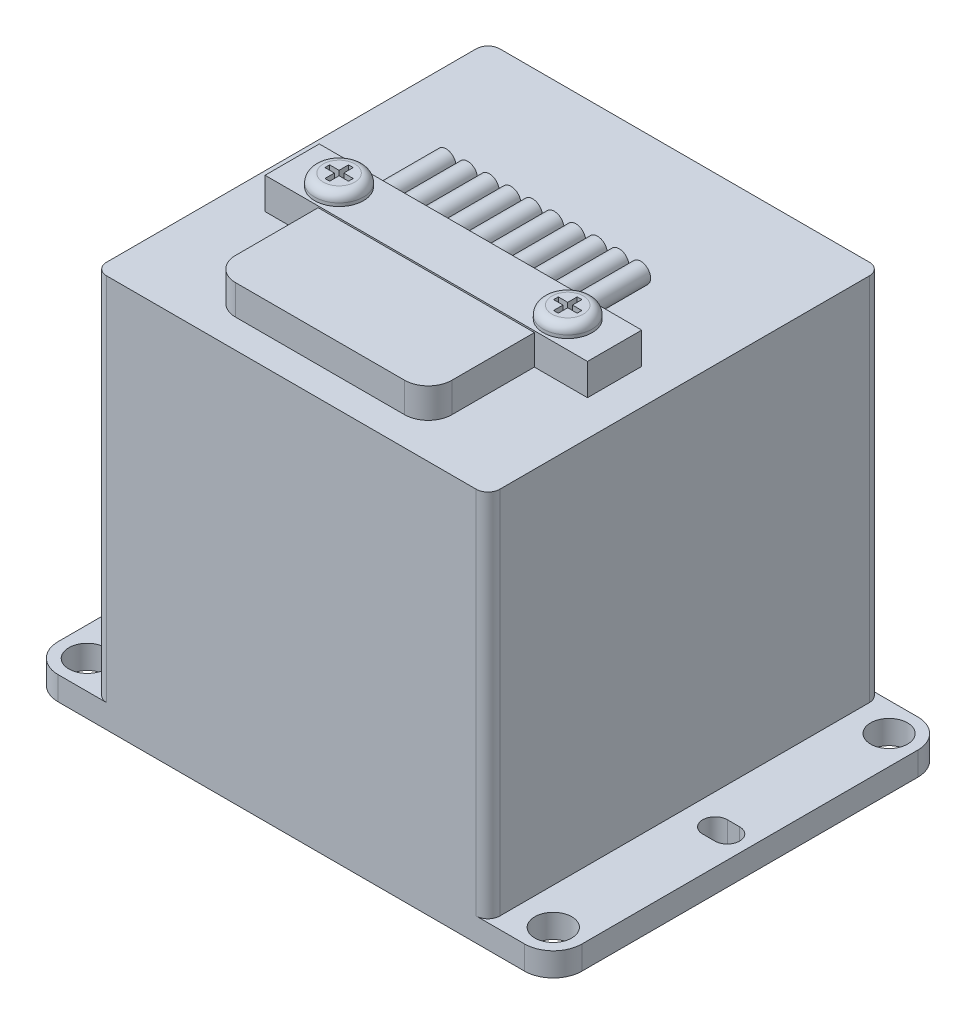
SolidWorks part; units mm, degrees
ref_plane "Front Plane" through (0, 0, 0) normal (0, 0, 1) x (1, 0, 0)
ref_plane "Top Plane" through (0, 0, 0) normal (0, 1, 0) x (1, 0, 0)
ref_plane "Right Plane" through (0, 0, 0) normal (1, 0, 0) x (0, 0, -1)
sketch "Sketch1" plane through (0, 0, 0) normal (0, 1, 0) x (1, 0, 0)
  line L1 (-16.9164, -12.7) -> (16.9164, -12.7)
  line L2 (-16.9164, -12.7) -> (-16.9164, 12.7)
  line L3 (-16.9164, 12.7) -> (16.9164, 12.7)
  line L4 (16.9164, -12.7) -> (16.9164, 12.7)
  line L5 (-16.9164, -12.7) -> (16.9164, 12.7) construction
  line L6 (-16.9164, 12.7) -> (16.9164, -12.7) construction
  point P0 (0, 0)
  dimension "D1" = 33.8328
  dimension "D2" = 25.4
extrude "Boss-Extrude1" add sketch "Sketch1" along normal blind 1.524
fillet "Fillet1" radius 1.8542 4 edges at (-16.9164, 0.762, 12.7) (-16.9164, 0.762, -12.7) (16.9164, 0.762, -12.7) (16.9164, 0.762, 12.7)
sketch "Sketch2" plane through (0, 1.524, 0) normal (0, 1, 0) x (1, 0, 0)
  line L1 (22.9238, 0) -> (-20.7739, 0) construction
  line L2 (15.4559, -0.8001) -> (14.6685, -0.8001)
  line L3 (15.4559, 0.8001) -> (14.6685, 0.8001)
  line L4 (16.256, 0) -> (13.8684, 0) construction
  line L5 (15.4559, 0.8001) -> (14.6685, -0.8001) construction
  circle A0 centre (15.0622, -10.8458) radius 1.1938
  circle A1 centre (15.0622, 10.8458) radius 1.1938
  circle A2 centre (-15.0368, 10.8458) radius 1.1938
  circle A3 centre (-15.0368, -10.8458) radius 1.1938
  circle A4 centre (-15.0368, 0) radius 0.8001
  arc A5 (15.4559, -0.8001) -> (15.4559, 0.8001) centre (15.4559, 0) ccw
  arc A6 (14.6685, 0.8001) -> (14.6685, -0.8001) centre (14.6685, 0) ccw
  point P26 (15.0622, 0)
  dimension "D1" = 2.3876
  dimension "D2" = 30.099
  dimension "D3" = 21.6916
  dimension "D4" = 1.6002
  dimension "D5" = 2.3876
  dimension "D6" = 1.6002
extrude "Cut-Extrude1" cut sketch "Sketch2" against normal blind 1.524
sketch "Sketch3" plane through (0, 1.524, 0) normal (0, 1, 0) x (1, 0, 0)
  line L0 (15.0622, 12.7) -> (-15.0622, 12.7) construction
  line L1 (-12.7, -12.7) -> (12.7, -12.7)
  line L2 (-12.7, -12.7) -> (-12.7, 12.7)
  line L3 (-12.7, 12.7) -> (12.7, 12.7)
  line L4 (12.7, -12.7) -> (12.7, 12.7)
  line L5 (-12.7, -12.7) -> (12.7, 12.7) construction
  line L6 (-12.7, 12.7) -> (12.7, -12.7) construction
  point P0 (0, 0)
  dimension "D1" = 25.4
extrude "Boss-Extrude2" add sketch "Sketch3" along normal blind 23.876
fillet "Fillet2" radius 0.762 4 edges
sketch "Sketch4" plane through (0, 25.4, 0) normal (0, 1, 0) x (1, 0, 0)
  line L0 (0, -21.1361) -> (0, 22.6474) construction
  line L1 (10.414, -3.9878) -> (-10.414, -3.9878)
  line L2 (10.414, -3.9878) -> (10.414, -0.4826)
  line L3 (10.414, -0.4826) -> (-10.414, -0.4826)
  line L4 (-10.414, -3.9878) -> (-10.414, -0.4826)
  line L5 (6.985, -3.9878) -> (-6.985, -3.9878)
  circle A0 centre (15.0622, -10.8458) radius 1.1938 construction
  dimension "D1" = 6.858
  dimension "D4" = 20.828
  dimension "D5" = 3.5052
extrude "Boss-Extrude3" add sketch "Sketch4" along normal blind 2.032 contours L0 L1 L2 L3 | L5 L0 L3 L4 L1
sketch "Sketch5" plane through (0, 25.4, 0) normal (0, 1, 0) x (1, 0, 0)
  line L0 (10.414, -3.9878) -> (-10.414, -3.9878) construction
  line L1 (6.985, -3.9878) -> (-6.985, -3.9878)
  line L2 (6.985, -3.9878) -> (6.985, -10.8458)
  line L3 (6.985, -10.8458) -> (-6.985, -10.8458)
  line L4 (-6.985, -3.9878) -> (-6.985, -10.8458)
  line L5 (0, -21.6155) -> (0, 18.5425) construction
  line L6 (0, 0) -> (0, -16.8235) construction
  dimension "D1" = 6.858
  dimension "D2" = 13.97
extrude "Boss-Extrude4" add sketch "Sketch5" along normal blind 1.9304
fillet "Fillet3" radius 1.524 2 edges at (-6.985, 26.3652, 10.8458) (6.985, 26.3652, 10.8458)
sketch "Sketch6" plane through (0, 0, 0.4826) normal (0, 0, -1) x (-1, 0, 0)
  line L3 (0, 36.3189) -> (0, -1.8757) construction
  circle A0 centre (-4.8895, 26.5554) radius 0.635
  circle A1 centre (3.4925, 26.5554) radius 0.635
  circle A2 centre (4.8895, 26.5554) radius 0.635
  circle A3 centre (2.0955, 26.5554) radius 0.635
  circle A4 centre (-2.0955, 26.5554) radius 0.635
  circle A5 centre (0.6985, 26.5554) radius 0.635
  circle A6 centre (-3.4925, 26.5554) radius 0.635
  circle A7 centre (-0.6985, 26.5554) radius 0.635
  circle A8 centre (-6.2865, 26.5554) radius 0.635
  circle A9 centre (6.2865, 26.5554) radius 0.635
  dimension "D1" = 1.27
  dimension "D3" = 1.397
  dimension "D4" = 1.397
  dimension "D5" = 1.397
  dimension "D6" = 1.397
  dimension "D7" = 1.397
  dimension "D8" = 1.397
  dimension "D9" = 1.397
  dimension "D10" = 1.397
  dimension "D2" = 1.397
extrude "Boss-Extrude5" add sketch "Sketch6" along normal blind 4.064
sketch "Sketch7" plane through (0, 27.432, 0) normal (0, 1, 0) x (1, 0, 0)
  line L0 (0, -5.518) -> (0, 6.6896) construction
  line L3 (10.414, -2.2352) -> (-10.414, -2.2352) construction
  line L4 (10.414, -3.9878) -> (10.414, -0.4826) construction
  line L5 (-10.414, -3.9878) -> (-10.414, -0.4826) construction
  circle A0 centre (7.3853, -2.2352) radius 1.5761
  circle A1 centre (-7.3853, -2.2352) radius 1.5761
extrude "Boss-Extrude6" add sketch "Sketch7" along normal blind 0.762
fillet "Fillet4" radius 0.5588 2 edges at (-7.3853, 28.194, 3.8113) (7.3853, 28.194, 3.8113)
sketch "Sketch8" plane through (0, 28.194, 0) normal (0, 1, 0) x (1, 0, 0)
  line L0 (8.4026, -2.2352) -> (8.1473, -2.2352) construction
  line L1 (-7.3853, -3.2525) -> (-7.3853, -2.9972) construction
  line L2 (7.3853, -3.2525) -> (7.3853, -2.9972) construction
  line L3 (7.5377, -1.4732) -> (7.5377, -2.0828)
  line L4 (7.5377, -1.4732) -> (7.2329, -1.4732)
  line L5 (7.5377, -2.9972) -> (7.2329, -2.9972)
  line L6 (7.2329, -1.4732) -> (7.2329, -2.0828)
  line L7 (-7.2329, -2.3876) -> (-6.6233, -2.3876)
  line L9 (6.6233, -2.3876) -> (7.2329, -2.3876)
  line L10 (6.6233, -2.3876) -> (6.6233, -2.0828)
  line L11 (8.1473, -2.3876) -> (8.1473, -2.0828)
  line L12 (6.6233, -2.0828) -> (7.2329, -2.0828)
  line L13 (-8.1473, -2.2352) -> (-8.4026, -2.2352) construction
  line L14 (-7.5377, -2.3876) -> (-7.5377, -2.9972)
  line L15 (-7.3853, -3.2525) -> (-7.3853, -2.9972) construction
  line L16 (-7.2329, -1.4732) -> (-7.2329, -2.0828)
  line L17 (-7.2329, -1.4732) -> (-7.5377, -1.4732)
  line L18 (-7.2329, -2.9972) -> (-7.5377, -2.9972)
  line L19 (-7.5377, -1.4732) -> (-7.5377, -2.0828)
  line L22 (-8.1473, -2.3876) -> (-7.5377, -2.3876)
  line L23 (-8.1473, -2.3876) -> (-8.1473, -2.0828)
  line L24 (-6.6233, -2.3876) -> (-6.6233, -2.0828)
  line L25 (-8.1473, -2.0828) -> (-7.5377, -2.0828)
  line L28 (7.5377, -2.3876) -> (8.1473, -2.3876)
  line L30 (-7.3853, -1.4732) -> (-7.3853, -1.2179) construction
  line L31 (7.5377, -2.3876) -> (7.5377, -2.9972)
  line L32 (-7.3853, -1.4732) -> (-7.3853, -1.2179) construction
  line L33 (-7.2329, -2.0828) -> (-6.6233, -2.0828)
  line L34 (7.2329, -2.3876) -> (7.2329, -2.9972)
  line L35 (6.6233, -2.2352) -> (-6.6233, -2.2352) construction
  line L38 (7.3853, -1.4732) -> (7.3853, -1.2179) construction
  line L39 (7.5377, -2.0828) -> (8.1473, -2.0828)
  line L41 (-7.2329, -2.3876) -> (-7.2329, -2.9972)
  circle A0 centre (7.3853, -2.2352) radius 1.0173 construction
  circle A1 centre (-7.3853, -2.2352) radius 1.0173 construction
  point P13 (7.3853, -2.2352)
  point P14 (7.3853, -2.2352)
  point P20 (-7.3853, -2.2352)
  point P25 (-7.3853, -2.2352)
  dimension "D1" = 0.3048
  dimension "D2" = 1.524
  dimension "D3" = 0.3048
  dimension "D4" = 1.524
  dimension "D5" = 1.524
  dimension "D6" = 0.3048
  dimension "D7" = 1.524
  dimension "D8" = 0.3048
extrude "Cut-Extrude2" cut sketch "Sketch8" against normal blind 0.762
